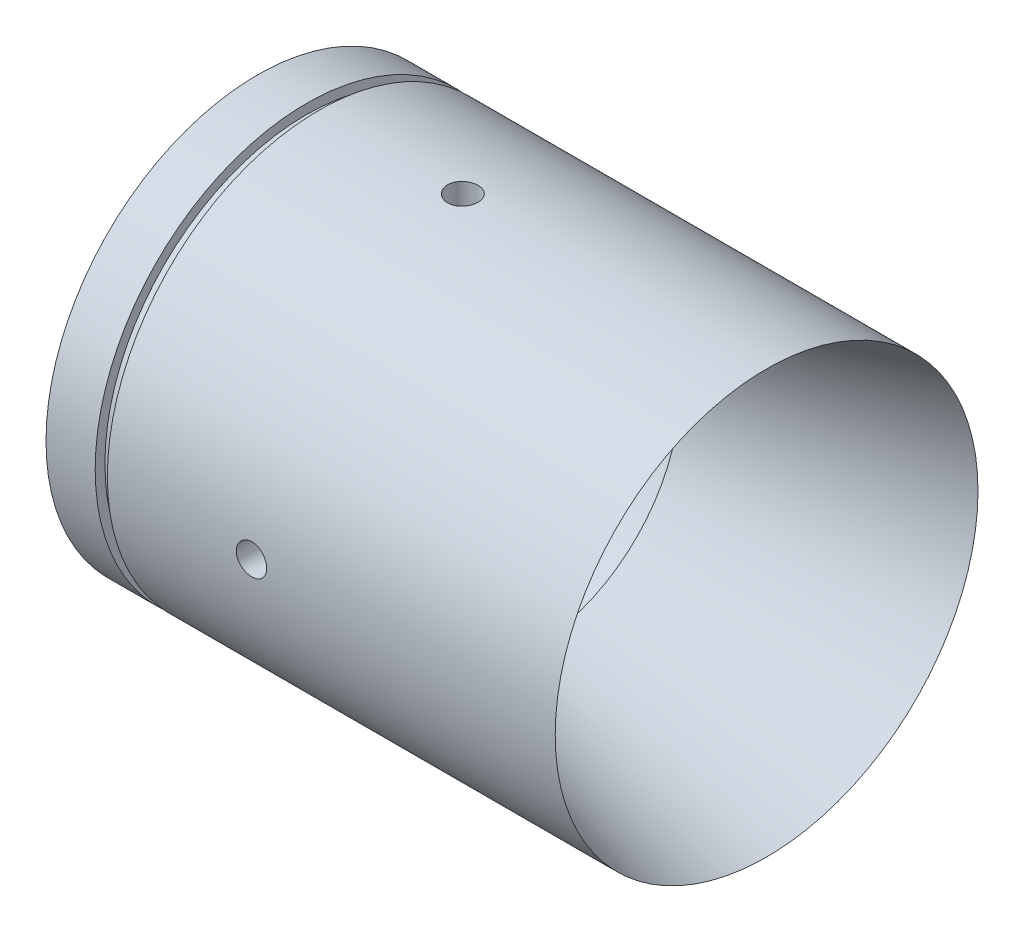
SolidWorks part; units mm, degrees
ref_plane "Front Plane" through (0, 0, 0) normal (0, 0, 1) x (1, 0, 0)
ref_plane "Top Plane" through (0, 0, 0) normal (0, 1, 0) x (1, 0, 0)
ref_plane "Right Plane" through (0, 0, 0) normal (1, 0, 0) x (0, 0, -1)
sketch "Sketch1" plane through (0, 0, 0) normal (0, 0, 1) x (1, 0, 0)
  line L0 (0, 0) -> (75.0218, 0) construction
  line L1 (0, 0) -> (0, 34.798) construction
  line L2 (11.6269, 34.798) -> (19.7237, 34.798) construction
  line L6 (11.6269, 34.798) -> (19.7237, 34.798)
  line L7 (11.6269, 34.798) -> (11.6269, 31.0015)
  line L8 (11.6269, 31.0015) -> (29.4966, 26.9446)
  line L9 (29.4966, 26.9446) -> (56.7358, 26.9446)
  line L10 (56.7358, 26.9446) -> (56.7358, 24.4266)
  line L11 (19.7237, 34.798) -> (19.7237, 33.198)
  line L12 (19.7237, 33.198) -> (21.7237, 33.198)
  line L13 (21.7237, 33.198) -> (21.7237, 34.798)
  line L14 (21.7237, 34.798) -> (60.6226, 34.798) construction
  line L15 (21.7237, 34.798) -> (95.4423, 34.798)
  line L20 (56.7358, 24.4266) -> (95.4423, 34.798)
  dimension "D1" = 34.798
  dimension "D6" = 2
  dimension "D7" = 1.6
revolve "Revolve1" add sketch "Sketch1" angle 360 about L0
ref_plane "Plane1" through (0, 34.798, 0) normal (0, 1, 0) x (1, 0, 0)
sketch "Sketch2" plane through (0, 34.798, 0) normal (0, 1, 0) x (1, 0, 0)
  line L0 (0, 0) -> (75.0218, 0) construction
  line L1 (95.4423, -34.798) -> (95.4423, 34.798) construction
  circle A0 centre (45.4423, 0) radius 2.5
  dimension "D2" = 5
  dimension "D1" = 50
extrude "Cut-Extrude1" cut sketch "Sketch2" against normal blind 5 contours A0
pattern_circular "CirPattern1" count 4 over 360 about axis through (0, 0, 0) along (1, 0, 0) of "Cut-Extrude1"
